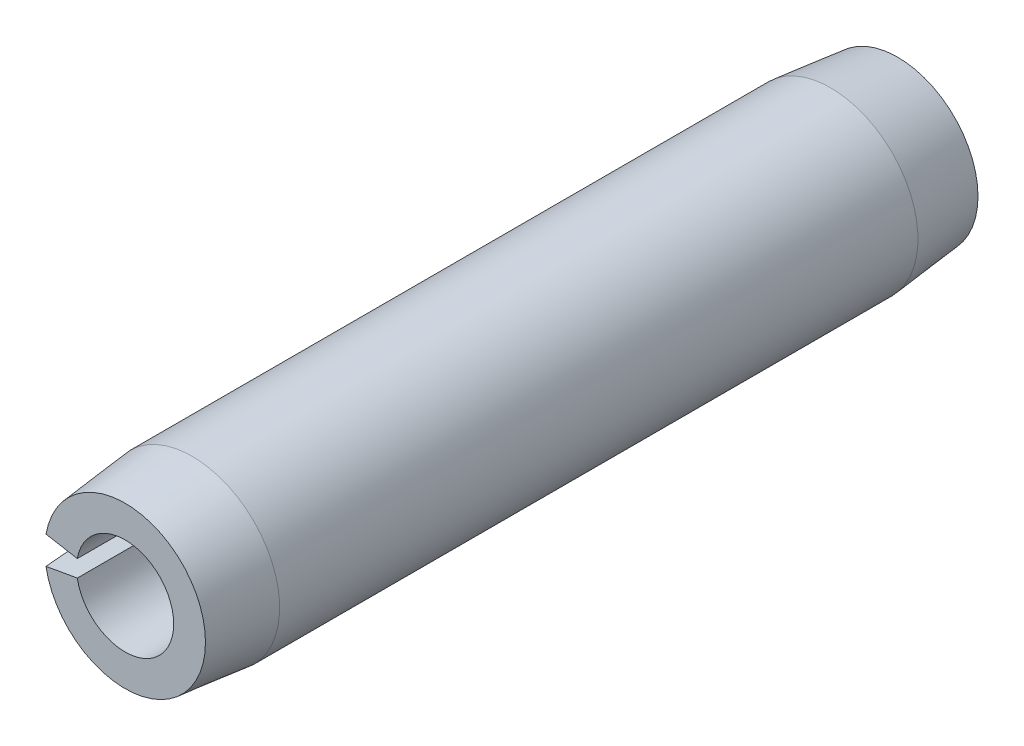
SolidWorks part; units mm, degrees
ref_plane "Front Plane" through (0, 0, 0) normal (0, 0, 1) x (1, 0, 0)
ref_plane "Top Plane" through (0, 0, 0) normal (0, 1, 0) x (1, 0, 0)
ref_plane "Right Plane" through (0, 0, 0) normal (1, 0, 0) x (0, 0, -1)
sketch "Sketch1" plane through (0, 0, 0) normal (0, 0, 1) x (1, 0, 0)
  line L0 (0.6985, 0) -> (1.2573, 0) construction
  line L1 (-1.2382, 0.2183) -> (-0.6879, 0.1213)
  line L2 (-0.6879, -0.1213) -> (-1.2382, -0.2183)
  arc A0 (-1.2382, -0.2183) -> (-1.2382, 0.2183) centre (0, 0) ccw
  arc A1 (-0.6879, -0.1213) -> (-0.6879, 0.1213) centre (0, 0) ccw
  dimension "OD" = 2.5146
  dimension "Wall thickness" = 0.5588
  dimension "D3" = 20
extrude "Extrude1" add sketch "Sketch1" along normal mid plane 11.1125
sketch "Sketch2" plane through (0, 0, 0) normal (1, 0, 0) x (0, 0, -1)
  line L0 (0, -1.2573) -> (0, 1.2573) construction
  line L1 (5.5562, 0) -> (-5.5562, 0) construction
  line L2 (5.5562, -0.6985) -> (5.5562, 0.6985) construction
  line L3 (5.5562, 1.2573) -> (-5.5562, 1.2573) construction
  line L4 (5.5562, 1.2573) -> (5.5562, 1.1557)
  line L5 (5.5562, 1.1557) -> (4.591, 1.2573)
  line L6 (4.591, 1.2573) -> (5.5562, 1.2573)
  line L7 (5.5562, -1.2573) -> (5.5562, 1.2573) construction
  line L8 (-4.591, 1.2573) -> (-5.5562, 1.2573)
  line L9 (-5.5562, 1.1557) -> (-4.591, 1.2573)
  line L10 (-5.5562, 1.2573) -> (-5.5562, 1.1557)
  line L11 (4.591, -1.2573) -> (5.5562, -1.2573) construction
  line L12 (5.5562, -1.1557) -> (4.591, -1.2573) construction
  line L13 (5.5562, -1.2573) -> (5.5562, -1.1557) construction
  dimension "B" = 2.3114
  dimension "Chamfer max" = 0.9652
revolve "Cut-Revolve1" cut sketch "Sketch2" angle 360 about L1
sketch "Sketch3" plane through (0, 0, 0) normal (0, 0, 1) x (1, 0, 0)
  line L0 (0.6985, 0) -> (1.2573, 0) construction
  line L1 (0.6985, 0) -> (1.2573, 0)
  circle A0 centre (0, 0) radius 1.2573
  circle A1 centre (0, 0) radius 0.6985
  arc A2 (-1.2382, -0.2183) -> (-1.2382, 0.2183) centre (0, 0) ccw construction
  arc A3 (-0.6879, -0.1213) -> (-0.6879, 0.1213) centre (0, 0) ccw construction
